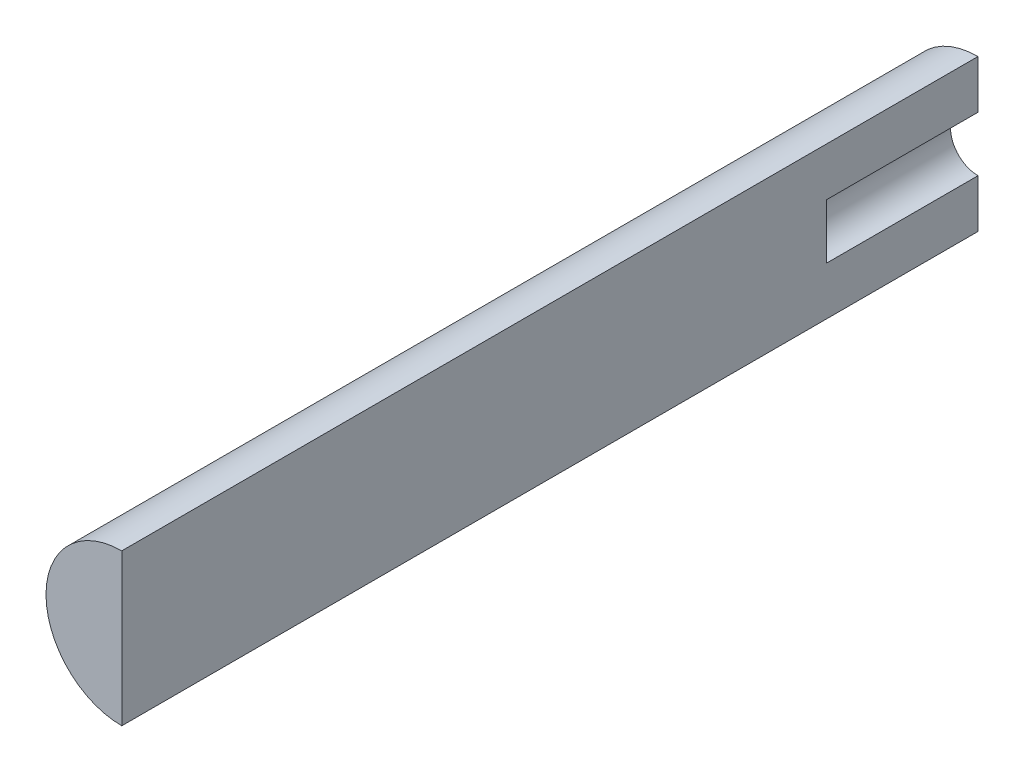
SolidWorks part; units mm, degrees
ref_plane "前视基准面" through (0, 0, 0) normal (0, 0, 1) x (1, 0, 0)
ref_plane "上视基准面" through (0, 0, 0) normal (0, 1, 0) x (1, 0, 0)
ref_plane "右视基准面" through (0, 0, 0) normal (1, 0, 0) x (0, 0, -1)
other "Configuration Table"
sketch "草图1" plane through (0, 0, 0) normal (0, 0, 1) x (1, 0, 0)
  circle A0 centre (0, 0) radius 4
  dimension "D1" = 8
extrude "凸台-拉伸1" add sketch "草图1" along normal blind 45.2
sketch "草图4" plane through (0, 0, 0) normal (0, 0, -1) x (-1, 0, 0)
  circle A0 centre (0, 0) radius 1.45
  dimension "D1" = 2.9
extrude "切除-拉伸3" cut sketch "草图4" against normal blind 8
sketch "草图5" plane through (0, 0, 0) normal (0, 0, -1) x (-1, 0, 0)
  line L1 (0, -4) -> (0, 4)
  circle A0 centre (0, 0) radius 4 construction
  arc A1 (0, 4) -> (0, -4) centre (0, 0) ccw
extrude "切除-拉伸4" cut sketch "草图5" against normal blind 60
